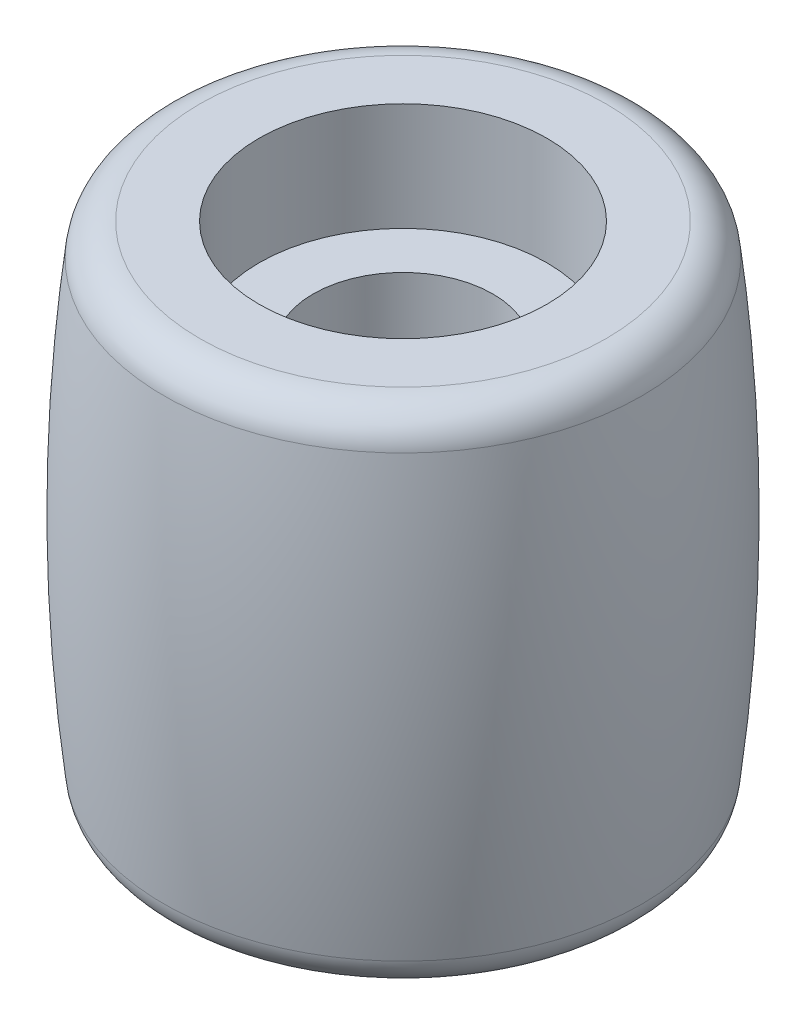
SolidWorks part; units mm, degrees
material "Silicon Rubber"
ref_plane "Front" through (0, 0, 0) normal (0, 0, 1) x (1, 0, 0)
ref_plane "Top" through (0, 0, 0) normal (0, 1, 0) x (1, 0, 0)
ref_plane "Right" through (0, 0, 0) normal (1, 0, 0) x (0, 0, -1)
sketch "Sketch1" plane through (0, 0, 0) normal (0, 0, 1) x (1, 0, 0)
  line L0 (45.5, 50.1304) -> (45.5, -50.6633) construction
  line L1 (0, 0) -> (52.5, 0) construction
  line L2 (29.6546, 7) -> (67.5949, 7)
  line L3 (29.6546, -7) -> (67.5949, -7)
  line L4 (45.5, 7) -> (45.5, -7)
  circle A0 centre (0, 0) radius 52.5
  dimension "D1" = 105
  dimension "D2" = 45.5
  dimension "D3" = 7
revolve "Revolve2" add sketch "Sketch1" angle 360 about L0
fillet "Fillet1" radius 1 2 edges at (52.0312, -7, 0) (52.0312, 7, 0)
sketch "Sketch2" plane through (0, -7, 0) normal (0, -1, 0) x (1, 0, 0)
  circle A0 centre (45.5, 0) radius 2.5
  dimension "D1" = 5
extrude "Cut-Extrude1" cut sketch "Sketch2" against normal through all
sketch "Sketch3" plane through (0, 7, 0) normal (0, 1, 0) x (1, 0, 0)
  circle A0 centre (45.5, 0) radius 4
  dimension "D1" = 8
extrude "Cut-Extrude2" cut sketch "Sketch3" against normal blind 3
sketch "Sketch4" plane through (0, -7, 0) normal (0, -1, 0) x (1, 0, 0)
  circle A0 centre (45.5, 0) radius 4
  dimension "D1" = 8
extrude "Cut-Extrude3" cut sketch "Sketch4" against normal blind 3
